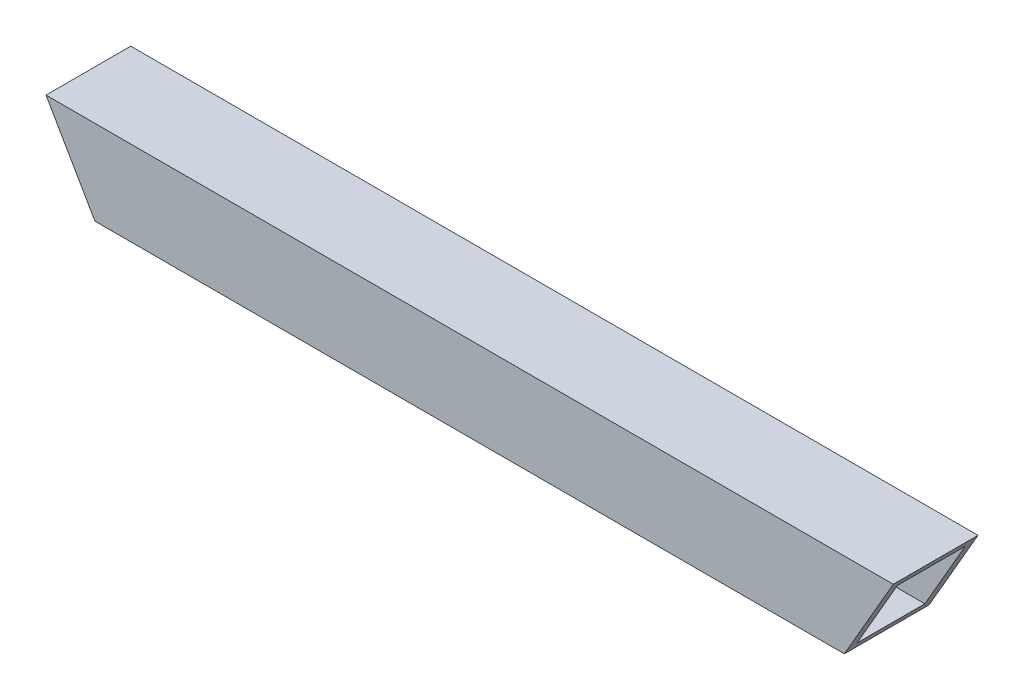
SolidWorks part; units mm, degrees
material "Ti-6Al-4VSolution treated and aged (SS)"
ref_plane "Front Plane" through (0, 0, 0) normal (0, 0, 1) x (1, 0, 0)
ref_plane "Top Plane" through (0, 0, 0) normal (0, 1, 0) x (1, 0, 0)
ref_plane "Right Plane" through (0, 0, 0) normal (1, 0, 0) x (0, 0, -1)
sketch "Sketch3" plane through (0, 0, 0) normal (0, 0, 1) x (1, 0, 0)
  line L0 (0, 0) -> (-500, 0)
  line L1 (-500, 0) -> (-471.1325, -50)
  line L2 (-471.1325, -50) -> (-28.8675, -50)
  line L3 (-28.8675, -50) -> (0, 0)
  dimension "D1" = 500
  dimension "D2" = 50
  dimension "D3" = 60
  dimension "D4" = 60
extrude "Boss-Extrude1" add sketch "Sketch3" along normal blind 50 contours L0 L1 L2 L3
sketch "Sketch4" plane through (0, 0, 0) normal (0.866, -0.5, 0) x (0, 0, -1)
  line L0 (-45, -5) -> (-5, -5)
  line L1 (-5, -5) -> (-5, -52.735)
  line L2 (-5, -52.735) -> (-45, -52.735)
  line L3 (-45, -52.735) -> (-45, -5)
  line L4 (0, -57.735) -> (0, 0) construction
  line L5 (-50, 0) -> (0, 0) construction
  line L6 (-50, -57.735) -> (-50, 0) construction
  line L7 (-50, -57.735) -> (0, -57.735) construction
  dimension "D1" = 5
  dimension "D2" = 5
  dimension "D3" = 5
  dimension "D4" = 5
extrude "Cut-Extrude1" cut sketch "Sketch4" along direction (-1, 0, 0) on the side against the normal through all
